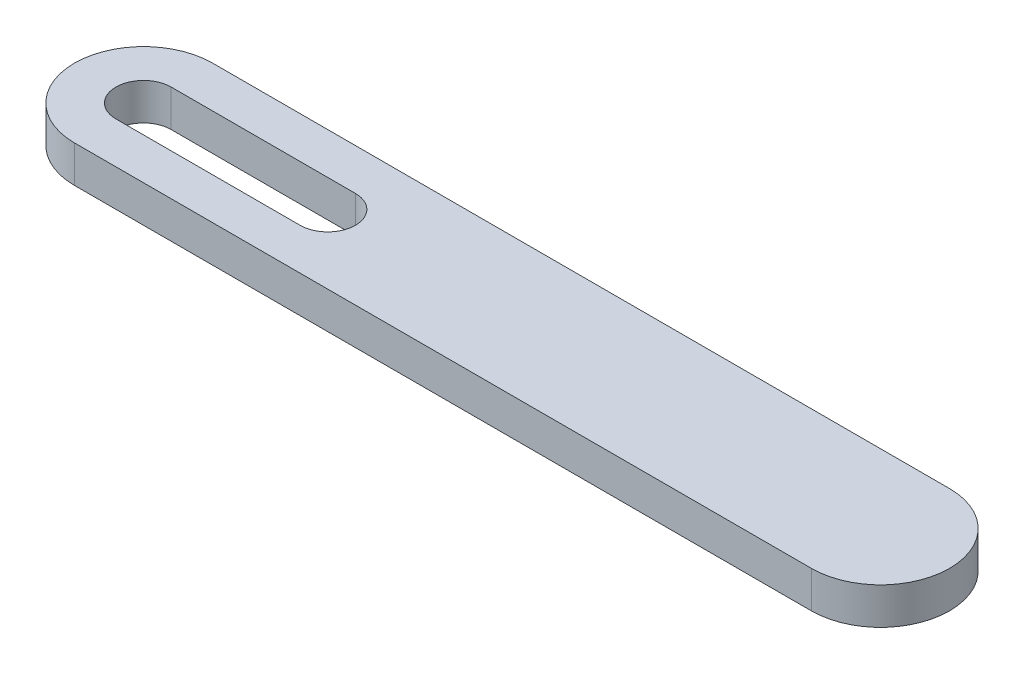
SolidWorks part; units mm, degrees
ref_plane "Front Plane" through (0, 0, 0) normal (0, 0, 1) x (1, 0, 0)
ref_plane "Top Plane" through (0, 0, 0) normal (0, 1, 0) x (1, 0, 0)
ref_plane "Right Plane" through (0, 0, 0) normal (1, 0, 0) x (0, 0, -1)
sketch "Sketch1" plane through (0, 0, 0) normal (0, 1, 0) x (1, 0, 0)
  line L0 (0, 0) -> (400, 0)
  line L1 (0, 75) -> (400, 75)
  line L2 (400, 75) -> (400, 0) construction
  line L3 (0, 37.5) -> (100, 37.5) construction
  line L4 (0, 52.5) -> (100, 52.5)
  line L5 (0, 22.5) -> (100, 22.5)
  arc A0 (400, 75) -> (400, 0) centre (400, 37.5) cw
  arc A1 (0, 75) -> (0, 0) centre (0, 37.5) ccw
  arc A2 (0, 52.5) -> (0, 22.5) centre (0, 37.5) ccw
  arc A3 (100, 22.5) -> (100, 52.5) centre (100, 37.5) ccw
  point P6 (50, 37.5)
  dimension "D1" = 400
  dimension "75/2" = 37.5
  dimension "D2" = 15
  dimension "D3" = 100
extrude "Boss-Extrude1" add sketch "Sketch1" along normal blind 20
